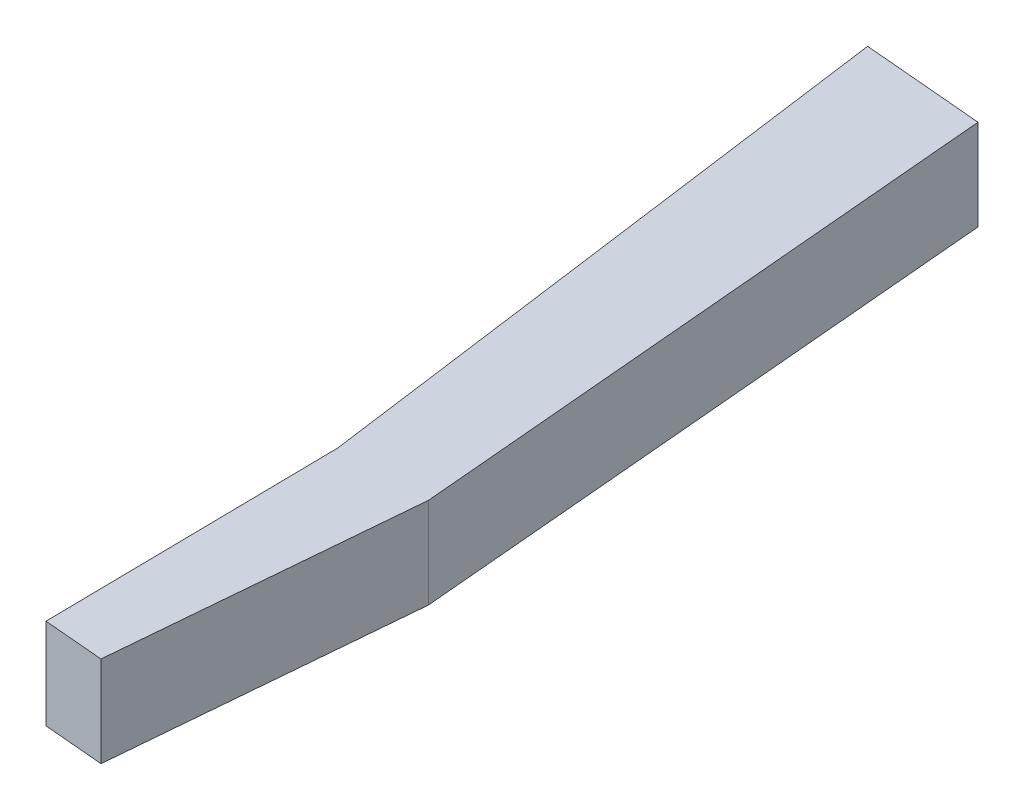
SolidWorks part; units mm, degrees
ref_plane "Front Plane" through (0, 0, 0) normal (0, 0, 1) x (1, 0, 0)
ref_plane "Top Plane" through (0, 0, 0) normal (0, 1, 0) x (1, 0, 0)
ref_plane "Right Plane" through (0, 0, 0) normal (1, 0, 0) x (0, 0, -1)
sketch "Sketch2" plane through (0, 0, 0) normal (0, 1, 0) x (1, 0, 0)
  line L0 (6.2844, 99.6195) -> (15, 0)
  line L1 (15, 0) -> (10.6422, -49.8097)
  line L2 (10.6422, -49.8097) -> (0.6803, -48.9382)
  line L3 (0.6803, -48.9382) -> (0, 0)
  line L4 (0, 0) -> (-13.7156, 101.3692)
  line L5 (-13.7156, 101.3692) -> (6.2844, 99.6195)
  line L6 (-15, 0) -> (15, 0) construction
  point P2 (0, 0)
  point P7 (0, 0)
  point P9 (0, 0)
  point P10 (0, 0)
  point P11 (0, 0)
  dimension "D1" = 10
  dimension "D2" = 20
  dimension "D3" = 85
  dimension "D4" = 85
  dimension "D5" = 15
  dimension "D6" = 50
  dimension "D8" = 100
extrude "Boss-Extrude1" add sketch "Sketch2" along normal blind 15 contours L4 L5 L0 L1 L2 L3
sketch "Sketch4" plane through (0, 15, 0) normal (0, 1, 0) x (1, 0, 0)
  line L0 (-10.2396, 98.0537) -> (3.0273, 0)
  line L1 (3.0273, 0) -> (3.0273, -46.1321)
  line L2 (3.0273, -46.1321) -> (7.9151, -46.5597)
  line L3 (7.9151, -46.5597) -> (11.9885, 0)
  line L4 (11.9885, 0) -> (3.5152, 96.8503)
  line L5 (3.5152, 96.8503) -> (-10.2396, 98.0537)
  line L6 (0, 0) -> (-13.7156, 101.3692) construction
  line L7 (6.2844, 99.6195) -> (15, 0) construction
  line L8 (-13.7156, 101.3692) -> (6.2844, 99.6195) construction
  line L9 (10.6422, -49.8097) -> (0.6803, -48.9382) construction
  line L10 (15, 0) -> (10.6422, -49.8097) construction
  line L11 (7.9151, -46.5597) -> (3.0273, -40.1321)
  line L12 (0, 0) -> (15, 0) construction
  line L13 (8.1074, -44.3616) -> (3.0273, -37.8581)
  line L14 (3.0273, -37.8581) -> (9.3056, -30.6658)
  dimension "D1" = 3
  dimension "D2" = 3
  dimension "D3" = 3
  dimension "D4" = 3
  dimension "D5" = 6
  dimension "D6" = 0.744
